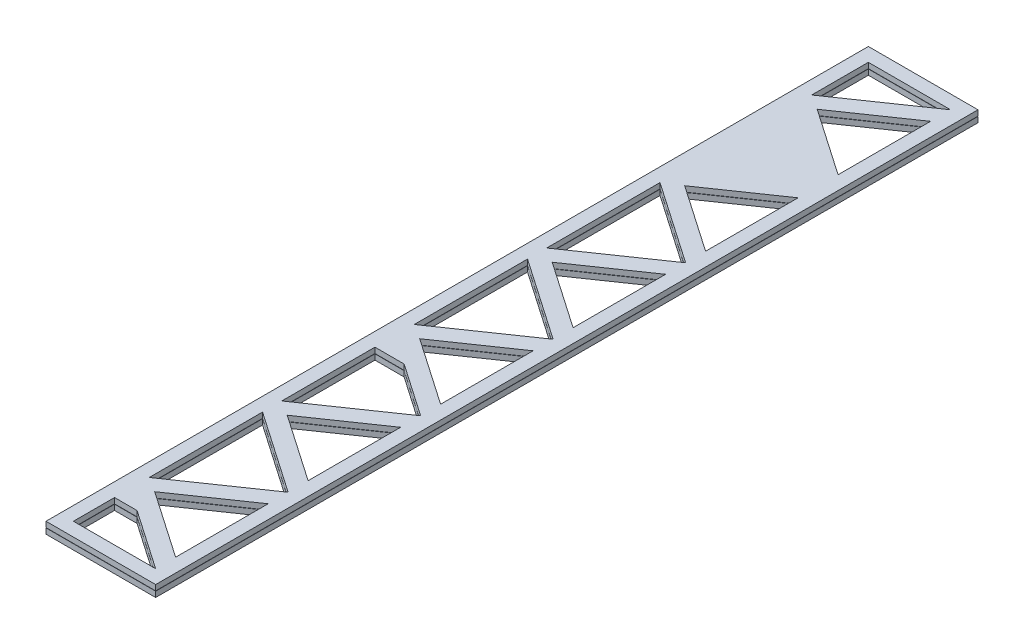
SolidWorks part; units mm, degrees
material "轻木"
ref_plane "前视基准面" through (0, 0, 0) normal (0, 0, 1) x (1, 0, 0)
ref_plane "上视基准面" through (0, 0, 0) normal (0, 1, 0) x (1, 0, 0)
ref_plane "右视基准面" through (0, 0, 0) normal (1, 0, 0) x (0, 0, -1)
other "Configuration Table"
sketch "草图2" plane through (0, 0, 762.01) normal (0, 0, 1) x (1, 0, 0)
  line L0 (130.7876, -3.3397) -> (130.7876, -3.4397) construction
  line L1 (130.7876, -1.3397) -> (170.7876, -1.3397)
  line L2 (130.7876, -1.3397) -> (130.7876, -3.3397)
  line L3 (130.7876, -3.3397) -> (170.7876, -3.3397)
  line L4 (170.7876, -1.3397) -> (170.7876, -3.3397)
  line L5 (130.7876, -3.4397) -> (170.7876, -3.4397)
  line L6 (130.7876, -3.4397) -> (130.7876, -5.4397)
  line L7 (130.7876, -5.4397) -> (170.7876, -5.4397)
  line L8 (170.7876, -3.4397) -> (170.7876, -5.4397)
  point P4 (130.7876, -3.3897)
  dimension "D1" = 2
  dimension "D2" = 40
  dimension "D3" = 2
  dimension "D4" = 40
  dimension "D5" = 0.1
extrude "凸台-拉伸1" add sketch "草图2" along normal blind 300
sketch "草图3" plane through (0, -1.3397, 0) normal (0, 1, 0) x (1, 0, 0)
  line L0 (165.7876, -1057.01) -> (165.7876, -767.01)
  line L1 (165.7876, -767.01) -> (135.7876, -767.01)
  line L2 (135.7876, -767.01) -> (135.7876, -1057.01)
  line L3 (135.7876, -1057.01) -> (165.7876, -1057.01)
  line L4 (170.7876, -762.01) -> (130.7876, -762.01)
  line L5 (130.7876, -762.01) -> (130.7876, -1062.01)
  line L6 (130.7876, -1062.01) -> (170.7876, -1062.01)
  line L7 (170.7876, -1062.01) -> (170.7876, -762.01)
  line L8 (170.7876, -762.01) -> (130.7876, -762.01)
  line L9 (130.7876, -762.01) -> (130.7876, -1062.01)
  line L10 (130.7876, -1062.01) -> (170.7876, -1062.01)
  line L11 (170.7876, -1062.01) -> (170.7876, -762.01)
  line L12 (170.7876, -912.01) -> (130.7876, -912.01) construction
  line L13 (165.7876, -1057.01) -> (135.7876, -1036.3433)
  line L14 (135.7876, -1029.3433) -> (165.7876, -1008.6767)
  line L15 (165.7876, -1008.6767) -> (135.7876, -988.01)
  line L16 (135.7876, -981.01) -> (165.7876, -960.3433)
  line L17 (165.7876, -960.3433) -> (135.7876, -939.6767)
  line L18 (135.7876, -932.6767) -> (165.7876, -912.01)
  line L19 (165.7876, -1049.7241) -> (141.2833, -1032.8433)
  line L20 (141.2833, -1032.8433) -> (165.7876, -1015.9626)
  line L21 (165.7876, -953.0574) -> (141.2833, -936.1767)
  line L22 (141.2833, -984.51) -> (165.7876, -967.6292)
  line L23 (141.2833, -936.1767) -> (163.0951, -921.1507) construction
  line L24 (141.2833, -936.1767) -> (165.7876, -919.2959)
  line L25 (130.707, -936.1767) -> (159.6913, -916.2097) construction
  line L26 (169.1914, -1052.069) -> (141.2833, -1032.8433) construction
  line L27 (165.7876, -1001.3908) -> (141.2833, -984.51)
  line L28 (176.3639, -1008.6767) -> (141.2833, -984.51) construction
  line L29 (176.3639, -960.3433) -> (141.2833, -936.1767) construction
  line L30 (141.2833, -1032.8433) -> (176.3639, -1008.6767) construction
  line L31 (165.7876, -960.3433) -> (130.707, -936.1767) construction
  line L32 (141.2833, -984.51) -> (176.3639, -960.3433) construction
  line L33 (130.707, -984.51) -> (165.7876, -960.3433) construction
  line L34 (165.7876, -1008.6767) -> (130.707, -984.51) construction
  line L35 (130.707, -1032.8433) -> (165.7876, -1008.6767) construction
  line L36 (165.7876, -1057.01) -> (130.707, -1032.8433) construction
  line L37 (141.2833, -887.8433) -> (165.7876, -904.7241)
  line L38 (135.7876, -891.3433) -> (165.7876, -912.01)
  line L39 (165.7876, -870.9626) -> (141.2833, -887.8433)
  line L40 (165.7876, -863.6767) -> (135.7876, -884.3433)
  line L41 (135.7876, -843.01) -> (165.7876, -863.6767)
  line L42 (141.2833, -839.51) -> (165.7876, -856.3908)
  line L43 (165.7876, -822.6292) -> (141.2833, -839.51)
  line L44 (165.7876, -815.3433) -> (135.7876, -836.01)
  line L45 (135.7876, -794.6767) -> (165.7876, -815.3433)
  line L46 (165.7876, -767.01) -> (135.7876, -787.6767)
  line L47 (165.7876, -774.2959) -> (141.2833, -791.1767)
  line L48 (141.2833, -791.1767) -> (165.7876, -808.0574)
  line L49 (144.0134, -1042.01) -> (135.7876, -1042.01)
  line L50 (146.4328, -947.01) -> (135.7876, -947.01)
  dimension "D4" = 7
  dimension "D5" = 15
  dimension "D6" = 95
  dimension "D1" = 0
  dimension "D2" = 5
  dimension "D3" = 6
extrude "切除-拉伸1" cut sketch "草图3" against normal through all contours L46 L1 L2 | L47 L48 L0 | L41 L2 L40 | L0 L39 L37 | L38 L2 L18 | L24 L21 L0 | L16 L17 L2 | L27 L0 L22 | L14 L15 L2 | L20 L19 L0 | L3 L13 L2 | L0 L43 L42
